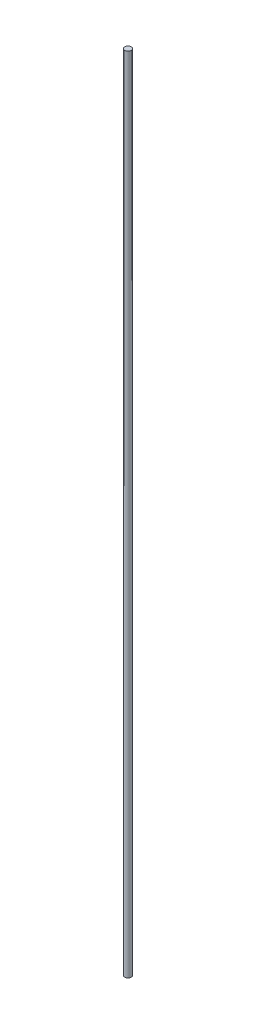
SolidWorks part; units mm, degrees
ref_plane "前视基准面" through (0, 0, 0) normal (0, 0, 1) x (1, 0, 0)
ref_plane "上视基准面" through (0, 0, 0) normal (0, 1, 0) x (1, 0, 0)
ref_plane "右视基准面" through (0, 0, 0) normal (1, 0, 0) x (0, 0, -1)
other "Configuration Table"
sketch "草图1" plane through (0, 0, 0) normal (0, 1, 0) x (1, 0, 0)
  circle A0 centre (0, 0) radius 2
  dimension "D1" = 4
extrude "凸台-拉伸1" add sketch "草图1" along normal blind 500
